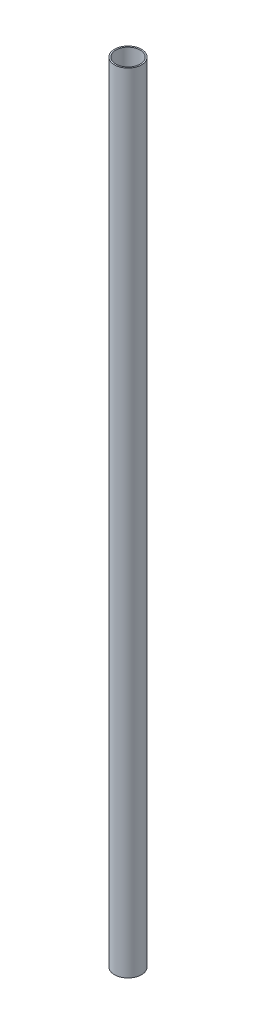
SolidWorks part; units mm, degrees
ref_plane "Front Plane" through (0, 0, 0) normal (0, 0, 1) x (1, 0, 0)
ref_plane "Top Plane" through (0, 0, 0) normal (0, 1, 0) x (1, 0, 0)
ref_plane "Right Plane" through (0, 0, 0) normal (1, 0, 0) x (0, 0, -1)
sketch "Sketch1" plane through (0, 0, 0) normal (0, 1, 0) x (1, 0, 0)
  circle A0 centre (0, 0) radius 5
  dimension "D1" = 10
sketch "Sketch2" plane through (0, 0, 0) normal (0, 0, 1) x (1, 0, 0)
  line L0 (0, 0) -> (0, 291)
  dimension "D1" = 291
sweep "Sweep1" add profiles "Sketch1" path "Sketch2"
shell "Shell1" thickness 0.5
